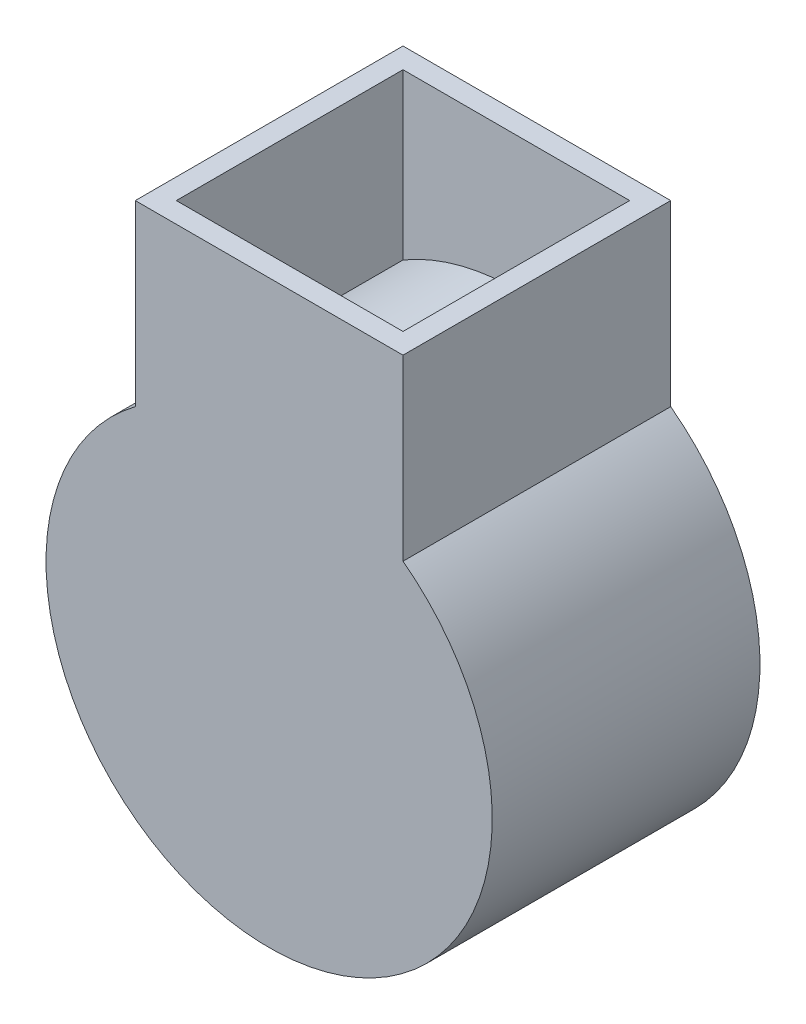
SolidWorks part; units mm, degrees
material "ABS"
ref_plane "Alzado" through (0, 0, 0) normal (0, 0, 1) x (1, 0, 0)
ref_plane "Planta" through (0, 0, 0) normal (0, 1, 0) x (1, 0, 0)
ref_plane "Vista lateral" through (0, 0, 0) normal (1, 0, 0) x (0, 0, -1)
sketch "Croquis1" plane through (0, 0, 0) normal (0, 0, 1) x (1, 0, 0)
  circle A0 centre (0, 0) radius 50
  dimension "D1" = 100
extrude "Saliente-Extruir1" add sketch "Croquis1" along normal mid plane 60
sketch "Croquis2" plane through (0, 0, -30) normal (0, 0, -1) x (-1, 0, 0)
  circle A0 centre (0, 0) radius 45
  circle A1 centre (0, 0) radius 32.5
  dimension "D1" = 90
  dimension "D2" = 65
extrude "Cortar-Extruir1" cut sketch "Croquis2" against normal blind 2
sketch "Croquis3" plane through (0, 0, -30) normal (0, 0, -1) x (-1, 0, 0)
  circle A0 centre (0, 0) radius 13
  dimension "D1" = 26
extrude "Cortar-Extruir2" cut sketch "Croquis3" against normal blind 6
ref_plane "Plano1" through (0, 80, 0) normal (0, 1, 0) x (1, 0, 0)
sketch "Croquis5" plane through (0, 80, 0) normal (0, 1, 0) x (1, 0, 0)
  line L1 (-25.4, -25.4) -> (25.4, -25.4)
  line L2 (-25.4, -25.4) -> (-25.4, 25.4)
  line L3 (-25.4, 25.4) -> (25.4, 25.4)
  line L4 (25.4, -25.4) -> (25.4, 25.4)
  line L5 (-25.4, -25.4) -> (25.4, 25.4) construction
  line L6 (-25.4, 25.4) -> (25.4, -25.4) construction
  line L7 (-30, -30) -> (30, -30)
  line L8 (-30, -30) -> (-30, 30)
  line L9 (-30, 30) -> (30, 30)
  line L10 (30, -30) -> (30, 30)
  line L11 (-30, -30) -> (30, 30) construction
  line L12 (-30, 30) -> (30, -30) construction
  point P0 (0, 0)
  point P6 (0, 0)
  dimension "D1" = 50.8
  dimension "D2" = 50.8
  dimension "D3" = 60
  dimension "D4" = 60
extrude "Saliente-Extruir2" add sketch "Croquis5" against normal up to next
